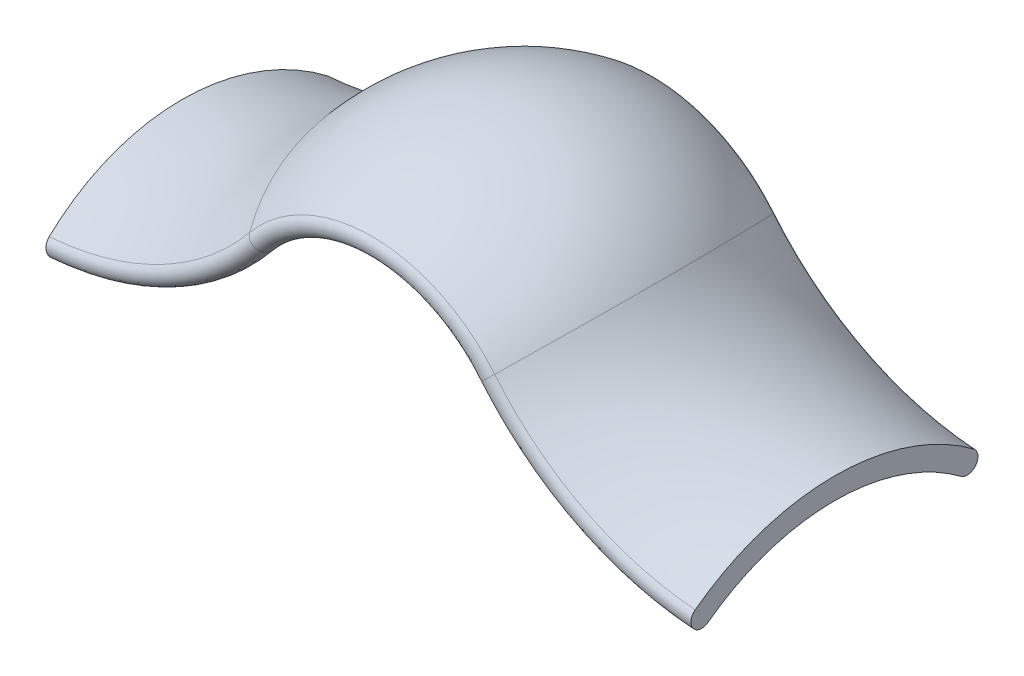
SolidWorks part; units mm, degrees
ref_plane "Front Plane" through (0, 0, 0) normal (0, 0, 1) x (1, 0, 0)
ref_plane "Top Plane" through (0, 0, 0) normal (0, 1, 0) x (1, 0, 0)
ref_plane "Right Plane" through (0, 0, 0) normal (1, 0, 0) x (0, 0, -1)
sketch "Sketch2" plane through (0, 0, 0) normal (1, 0, 0) x (0, 0, -1)
  arc A0 (14.8853, -2.4) -> (-14.8853, -2.4) centre (0, -22.3322) ccw
  arc A1 (-14.8853, -2.4) -> (-16.4051, -0.3649) centre (-15.6452, -1.3824) cw
  arc A2 (14.8853, -2.4) -> (16.4051, -0.3649) centre (15.6452, -1.3824) ccw
  arc A8 (16.4051, -0.3649) -> (-16.4051, -0.3649) centre (0, -22.3322) ccw
  arc A16 (-12.6566, -6.8742) -> (-9.5053, -6.0796) centre (0, -50.423) cw construction
  arc A17 (-9.5053, -6.0796) -> (-7.8363, -6.2917) centre (-8.9729, -8.5632) cw construction
  arc A18 (-7.8363, -6.2917) -> (7.8363, -6.2917) centre (0, 9.3694) ccw construction
  arc A19 (9.5053, -6.0796) -> (7.8363, -6.2917) centre (8.9729, -8.5632) ccw construction
  arc A20 (9.5053, -6.0796) -> (12.6566, -6.8742) centre (0, -50.423) cw construction
  arc A21 (-11.9477, -9.3133) -> (-8.9729, -8.5632) centre (0, -50.423) cw construction
  arc A22 (-8.9729, -8.5632) -> (8.9729, -8.5632) centre (0, 9.3694) ccw construction
  arc A23 (8.9729, -8.5632) -> (11.9477, -9.3133) centre (0, -50.423) cw construction
  arc A24 (8.9729, -8.5632) -> (8.9729, -8.5632) centre (8.9729, -8.5632) ccw construction
  arc A25 (-8.9729, -8.5632) -> (-8.9729, -8.5632) centre (-8.9729, -8.5632) cw construction
  arc A26 (-12.6566, -6.8742) -> (-14.8853, -2.4) centre (-13.3654, -4.4351) cw construction
  arc A27 (-11.9477, -9.3133) -> (-16.4051, -0.3649) centre (-13.3654, -4.4351) cw construction
  arc A28 (12.6566, -6.8742) -> (14.8853, -2.4) centre (13.3654, -4.4351) ccw construction
  arc A29 (11.9477, -9.3133) -> (16.4051, -0.3649) centre (13.3654, -4.4351) ccw construction
  point P0 (0, 0)
  point P15 (8.5874, -5.8927)
  dimension "D3" = 2.54
sketch "Sketch4" plane through (0, 0, 0) normal (0, 0, 1) x (1, 0, 0)
  line L0 (0, 0) -> (-76.2, 0) construction
  line L1 (-38.1, 0) -> (-38.1, 8.289) construction
  arc A0 (-23.3777, 12.0895) -> (-52.8223, 12.0895) centre (-38.1, 0) ccw
  arc A1 (0, 0) -> (-23.3777, 12.0895) centre (2.372, 33.2344) cw
  arc A2 (-76.2, 0) -> (-52.8223, 12.0895) centre (-78.572, 33.2344) ccw
  dimension "D1" = 19.05
  dimension "D2" = 76.2
sweep "Sweep1" add profiles "Sketch2" path "Sketch4"
sketch "Sketch7" plane through (0, 0, 0) normal (0, 1, 0) x (1, 0, 0)
  line L0 (0, 0) -> (-76.2, 0) construction
  line L2 (-38.1, 0) -> (-38.1, 9.6825) construction
  arc A0 (-72.647, 9.6757) -> (-72.647, -9.6757) centre (-111.4874, 0) cw
  arc A1 (-69.9936, 12.8226) -> (-72.647, 9.6757) centre (-70.1824, 10.2897) ccw
  arc A2 (-3.553, 9.6757) -> (-6.2064, 12.8226) centre (-6.0176, 10.2897) ccw
  arc A3 (-3.553, -9.6757) -> (-6.2064, -12.8226) centre (-6.0176, -10.2897) cw
  arc A4 (-3.553, 9.6757) -> (-3.553, -9.6757) centre (35.2874, 0) ccw
  arc A5 (-72.647, -9.6757) -> (-69.9936, -12.8226) centre (-70.1824, -10.2897) ccw
  arc A6 (-69.9936, 12.8226) -> (-6.2064, 12.8226) centre (-38.1, 440.8041) ccw
  arc A7 (-69.9936, -12.8226) -> (-6.2064, -12.8226) centre (-38.1, -440.8041) cw
  point P5 (-38.1, 0)
  dimension "D1" = 2.54
